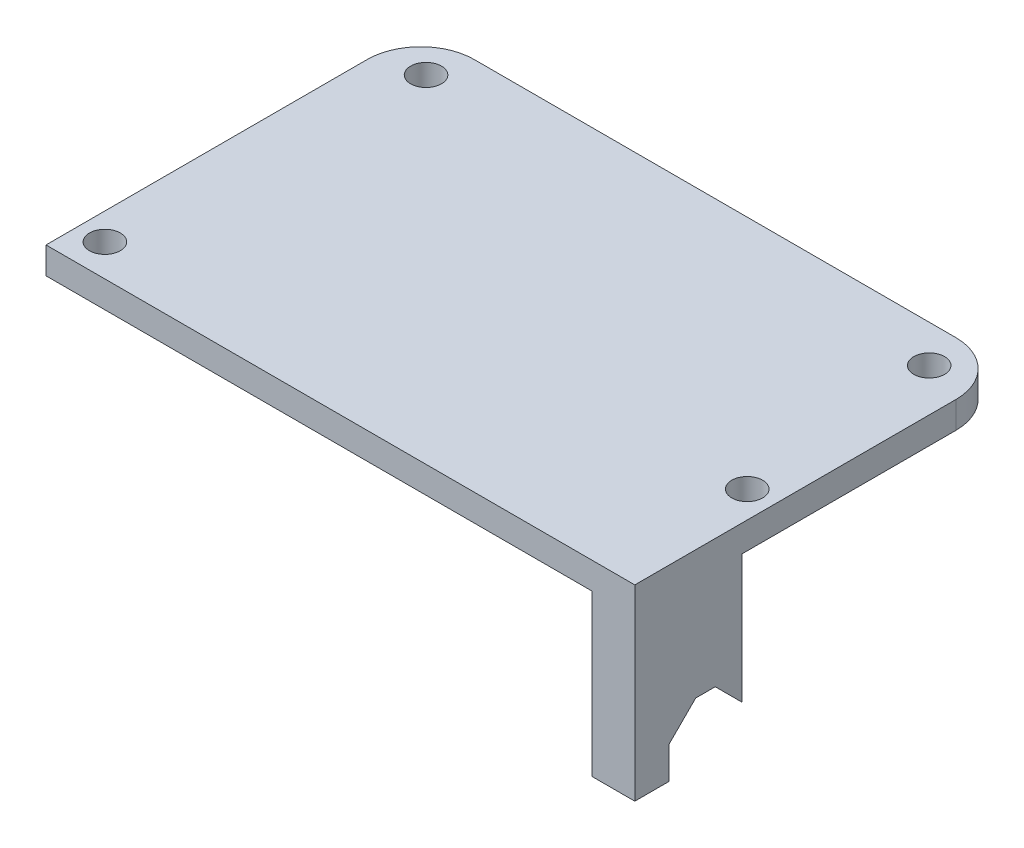
SolidWorks part; units mm, degrees
ref_plane "Front Plane" through (0, 0, 0) normal (0, 0, 1) x (1, 0, 0)
ref_plane "Top Plane" through (0, 0, 0) normal (0, 1, 0) x (1, 0, 0)
ref_plane "Right Plane" through (0, 0, 0) normal (1, 0, 0) x (0, 0, -1)
sketch "Sketch1" plane through (0, 0, 0) normal (0, 1, 0) x (1, 0, 0)
  line L0 (-12.2238, 0) -> (12.2238, 0) construction
  line L1 (-34.925, -22.225) -> (34.925, -22.225)
  line L2 (-34.925, -22.225) -> (-34.925, 22.225)
  line L3 (-34.925, 22.225) -> (34.925, 22.225)
  line L4 (34.925, -22.225) -> (34.925, 22.225)
  line L5 (-34.925, -22.225) -> (34.925, 22.225) construction
  line L6 (-34.925, 22.225) -> (34.925, -22.225) construction
  point P0 (0, 0)
  dimension "D1" = 69.85
  dimension "D2" = 44.45
extrude "Boss-Extrude1" add sketch "Sketch1" along normal blind 3.175
sketch "Sketch2" plane through (34.925, 0, 0) normal (1, 0, 0) x (0, 0, -1)
  line L0 (-22.225, 0) -> (-22.225, -19.05)
  line L1 (24.4475, 0) -> (-24.4475, 0) construction
  line L2 (-22.225, -19.05) -> (-18.161, -19.05)
  line L3 (-18.161, -19.05) -> (-18.161, -15.222)
  line L4 (-18.161, -15.222) -> (-15.0041, -12.065)
  line L5 (-15.0041, -12.065) -> (-12.682, -12.065)
  line L6 (-12.682, -12.065) -> (-9.525, -15.222)
  line L9 (-22.225, 0) -> (-9.525, 0)
  line L10 (-9.525, -15.222) -> (-9.525, 0)
  line L11 (-22.225, 3.175) -> (-22.225, 0) construction
  dimension "D1" = 12.065
  dimension "D2" = 19.05
  dimension "D3" = 2.3221
  dimension "D4" = 7.2209
  dimension "D5" = 12.7
  dimension "D6" = 4.064
extrude "Boss-Extrude2" add sketch "Sketch2" against normal blind 5.08 contours L6 L10 L9 L0 L2 L3 L4 L5
fillet "Fillet1" radius 6.35 2 edges at (-34.925, 1.5875, -22.225) (34.925, 1.5875, -22.225)
sketch "Sketch3" plane through (0, 0, 0) normal (0, -1, 0) x (1, 0, 0)
  point P0 (29.845, -17.78)
  point P1 (-29.845, -17.78)
  point P3 (-31.75, 18.415)
  point P5 (31.75, 5.715)
hole_wizard "#6 (0.204) Diameter Hole1" positions "Sketch4" profile "Sketch6" hole size "#6" standard "ANSI Inch"
sketch "Sketch4" plane through (0, 0, 0) normal (0, -1, 0) x (-1, 0, 0)
  point P0 (-29.845, 17.78)
  point P3 (29.845, 17.78)
  point P6 (31.75, -18.415)
  point P9 (-31.75, -5.715)
sketch "Sketch6" plane through (29.845, 0, -17.78) normal (1, 0, 0) x (0, 0, -1)
  line L0 (0, 0) -> (0, 39.1989)
  line L1 (0, 39.1989) -> (1.8288, 38.1)
  line L2 (1.8288, 38.1) -> (1.8288, 0)
  line L5 (1.8288, 0) -> (0, 0)
  line L10 (0, 39.1989) -> (-1.8288, 38.1) construction
  line L11 (0, -6.35) -> (0, 107.95) construction
  dimension "Hole Dia." = 3.6576
  dimension "Hole Depth" = 38.1
  dimension "Drill Angle" = 118
